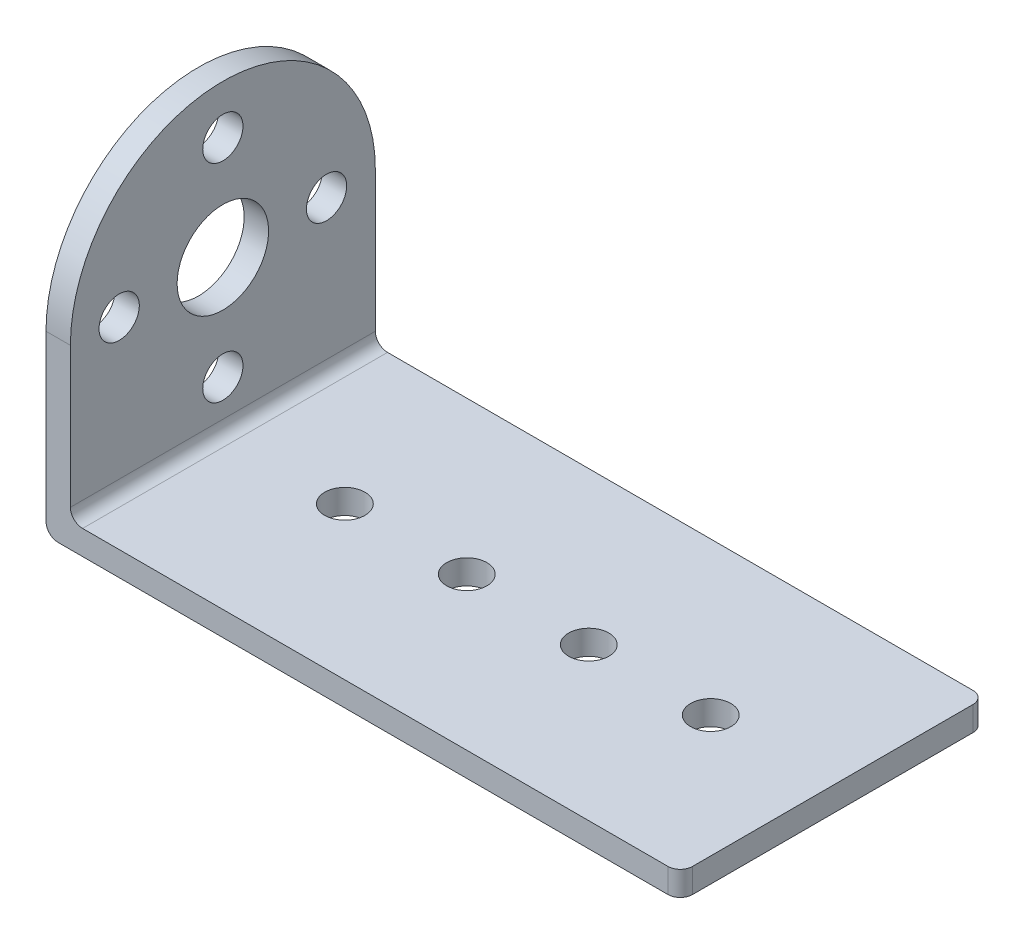
SolidWorks part; units mm, degrees
ref_plane "Front Plane" through (0, 0, 0) normal (0, 0, 1) x (1, 0, 0)
ref_plane "Top Plane" through (0, 0, 0) normal (0, 1, 0) x (1, 0, 0)
ref_plane "Right Plane" through (0, 0, 0) normal (1, 0, 0) x (0, 0, -1)
sketch "Sketch3" plane through (0, 0, 0) normal (0, 1, 0) x (1, 0, 0)
  line L1 (0, 0) -> (52, 0)
  line L2 (0, 0) -> (0, 25)
  line L3 (0, 25) -> (52, 25)
  line L4 (52, 0) -> (52, 25)
  dimension "D1" = 52
  dimension "D2" = 25
extrude "Boss-Extrude3" add sketch "Sketch3" along normal blind 2
sketch "Sketch4" plane through (0, 0, 0) normal (1, 0, 0) x (0, 0, -1)
  line L1 (25, 0) -> (0, 0)
  line L2 (25, 0) -> (25, 14.5)
  line L3 (25, 14.5) -> (0, 14.5)
  line L4 (0, 0) -> (0, 14.5)
  dimension "D1" = 14.5
  dimension "D2" = 25
extrude "Boss-Extrude4" add sketch "Sketch4" along normal blind 2
sketch "Sketch5" plane through (0, 0, 0) normal (-1, 0, 0) x (0, 0, 1)
  line L0 (-25, 14.5) -> (0, 14.5) construction
  line L8 (-25, 0) -> (0, 0)
  line L9 (0, 0) -> (0, 14.5)
  line L10 (0, 14.5) -> (-25, 14.5)
  line L11 (-25, 14.5) -> (-25, 0)
  line L12 (-25, 0) -> (0, 0)
  line L13 (0, 0) -> (0, 14.5)
  line L15 (-25, 14.5) -> (-25, 0)
  arc A0 (-25, 14.5) -> (0, 14.5) centre (-12.5, 14.5) cw
  dimension "D1" = 0
extrude "Boss-Extrude5" add sketch "Sketch5" against normal blind 2
sketch "Sketch6" plane through (0, 2, 0) normal (0, 1, 0) x (1, 0, 0)
  line L0 (2, 0) -> (52, 0) construction
  line L1 (2, 0) -> (2, 25) construction
  circle A0 centre (12, 12.5) radius 1.65
  circle A1 centre (22, 12.5) radius 1.65
  circle A2 centre (32, 12.5) radius 1.65
  circle A3 centre (42, 12.5) radius 1.65
  point P10 (2, 12.5)
  dimension "D1" = 3.3
  dimension "D2" = 3.3
  dimension "D3" = 3.3
  dimension "D4" = 3.3
  dimension "D5" = 12.5
  dimension "D6" = 12.5
  dimension "D7" = 12.5
  dimension "D8" = 12.5
  dimension "D9" = 10
  dimension "D10" = 20
  dimension "D11" = 10
  dimension "D12" = 10
extrude "Cut-Extrude1" cut sketch "Sketch6" against normal blind 2
sketch "Sketch7" plane through (0, 0, 0) normal (-1, 0, 0) x (0, 0, 1)
  line L0 (-25, 0) -> (0, 0) construction
  line L1 (0, 14.5) -> (0, 0) construction
  circle A0 centre (-12.5, 14.5) radius 3.75
  circle A1 centre (-21, 14.5) radius 1.65
  circle A2 centre (-4, 14.5) radius 1.65
  circle A3 centre (-12.5, 6) radius 1.65
  circle A4 centre (-12.5, 23) radius 1.65
  point P13 (-12.5, 0)
  dimension "D1" = 7.5
  dimension "D4" = 3.3
  dimension "D5" = 3.3
  dimension "D6" = 3.3
  dimension "D7" = 3.3
  dimension "D2" = 14.5
  dimension "D3" = 12.5
  dimension "D8" = 8.5
  dimension "D9" = 14.5
  dimension "D10" = 8.5
  dimension "D11" = 8.5
  dimension "D12" = 14.5
  dimension "D13" = 8.5
  dimension "D14" = 6
  dimension "D15" = 23
extrude "Cut-Extrude2" cut sketch "Sketch7" against normal blind 2
fillet "Fillet1" radius 1 4 edges at (2, 2, -12.5) (52, 1, 0) (52, 1, -25) (0, 0, -12.5)
